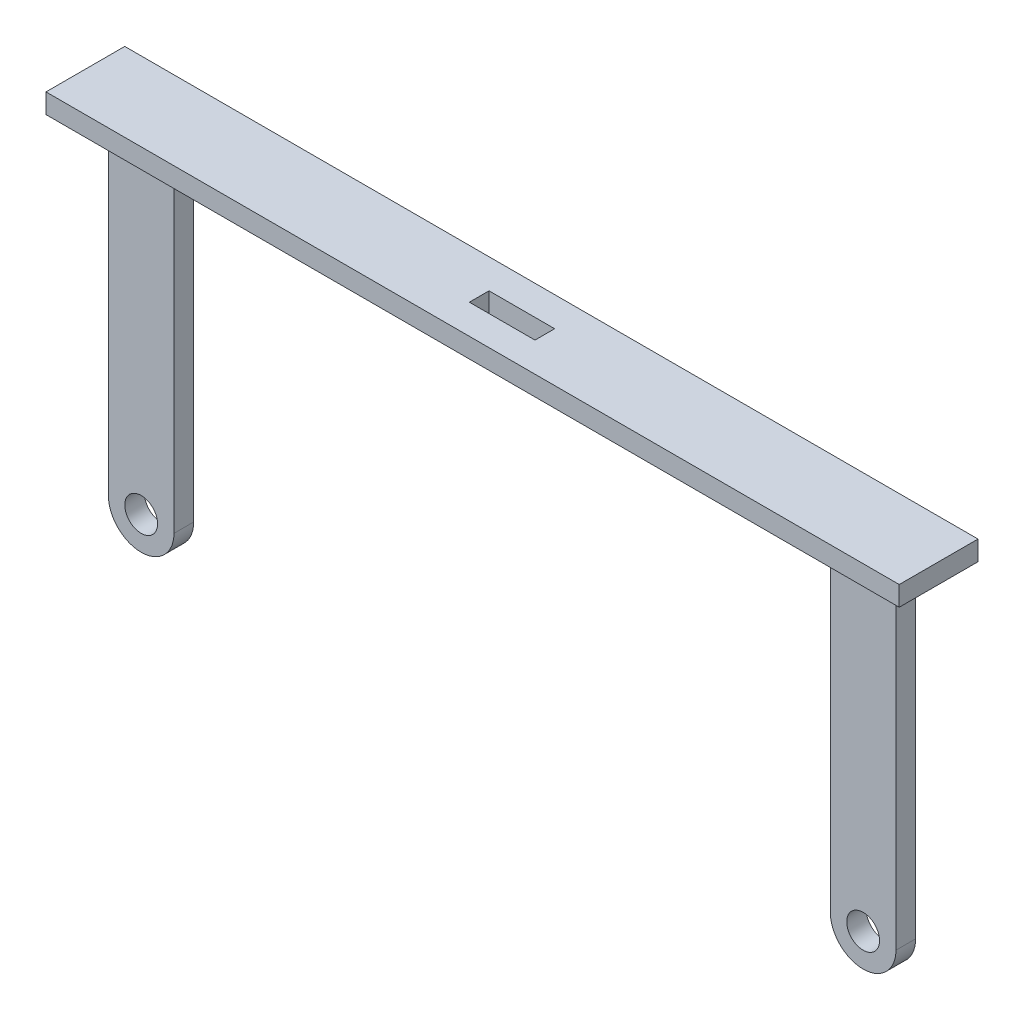
SolidWorks part; units mm, degrees
ref_plane "Front Plane" through (0, 0, 0) normal (0, 0, 1) x (1, 0, 0)
ref_plane "Top Plane" through (0, 0, 0) normal (0, 1, 0) x (1, 0, 0)
ref_plane "Right Plane" through (0, 0, 0) normal (1, 0, 0) x (0, 0, -1)
sketch "Sketch1" plane through (0, 0, 0) normal (0, 0, 1) x (1, 0, 0)
  line L0 (-60, -1.5) -> (-60, -51.5)
  line L1 (65, -1.5) -> (-65, -1.5)
  line L2 (65, -1.5) -> (65, 1.5)
  line L3 (65, 1.5) -> (-65, 1.5)
  line L4 (-65, -1.5) -> (-65, 1.5)
  line L5 (65, -1.5) -> (-65, 1.5) construction
  line L6 (65, 1.5) -> (-65, -1.5) construction
  line L7 (-60, -51.5) -> (-50, -51.5)
  line L8 (-50, -51.5) -> (-50, -1.5)
  line L9 (0, 8.3816) -> (0, -53.1459) construction
  line L10 (50, -51.5) -> (50, -1.5)
  line L11 (60, -1.5) -> (60, -51.5)
  arc A0 (-60, -51.5) -> (-50, -51.5) centre (-55, -51.5) ccw
  circle A1 centre (-55, -51.5) radius 2.5
  arc A2 (60, -51.5) -> (50, -51.5) centre (55, -51.5) cw
  circle A3 centre (55, -51.5) radius 2.5
  point P0 (0, 0)
  dimension "D6" = 5
  dimension "D1" = 130
  dimension "D2" = 3
  dimension "D3" = 50
  dimension "D4" = 10
  dimension "D5" = 50
extrude "Boss-Extrude1" add sketch "Sketch1" along normal blind 3 contours A1 L7 L8 L1 L0 | L4 L1 L2 L3 | A2 L11 L1 L10 A3 | A1 L7 A0
sketch "Sketch2" plane through (0, 1.5, 0) normal (0, 1, 0) x (1, 0, 0)
  line L0 (0, 0) -> (0, -3) construction
  line L1 (65, -3) -> (-65, -3) construction
  line L2 (-65, -1.5) -> (18.2783, -1.5) construction
  line L3 (-65, -3) -> (-65, 0) construction
  line L5 (65, -7.5) -> (-65, -7.5)
  line L6 (65, -7.5) -> (65, 4.5)
  line L7 (65, 4.5) -> (-65, 4.5)
  line L8 (-65, -7.5) -> (-65, 4.5)
  line L9 (65, -7.5) -> (-65, 4.5) construction
  line L10 (65, 4.5) -> (-65, -7.5) construction
  point P9 (0, -1.5)
  dimension "D1" = 12
extrude "Boss-Extrude2" add sketch "Sketch2" against normal blind 3
sketch "Sketch3" plane through (0, 1.5, 0) normal (0, 1, 0) x (1, 0, 0)
  line L0 (-65, -1.5) -> (65, -1.5) construction
  line L1 (-65, -7.5) -> (-65, 4.5) construction
  line L2 (65, -7.5) -> (65, 4.5) construction
  line L3 (0, 4.5) -> (0, -7.5) construction
  line L4 (65, 4.5) -> (-65, 4.5) construction
  line L5 (-65, -7.5) -> (65, -7.5) construction
  line L7 (5, -3) -> (-5, -3)
  line L8 (5, -3) -> (5, 0)
  line L9 (5, 0) -> (-5, 0)
  line L10 (-5, -3) -> (-5, 0)
  line L11 (5, -3) -> (-5, 0) construction
  line L12 (5, 0) -> (-5, -3) construction
  point P12 (0, -1.5)
  dimension "D1" = 10
  dimension "D2" = 3
extrude "Cut-Extrude1" cut sketch "Sketch3" against normal blind 3
